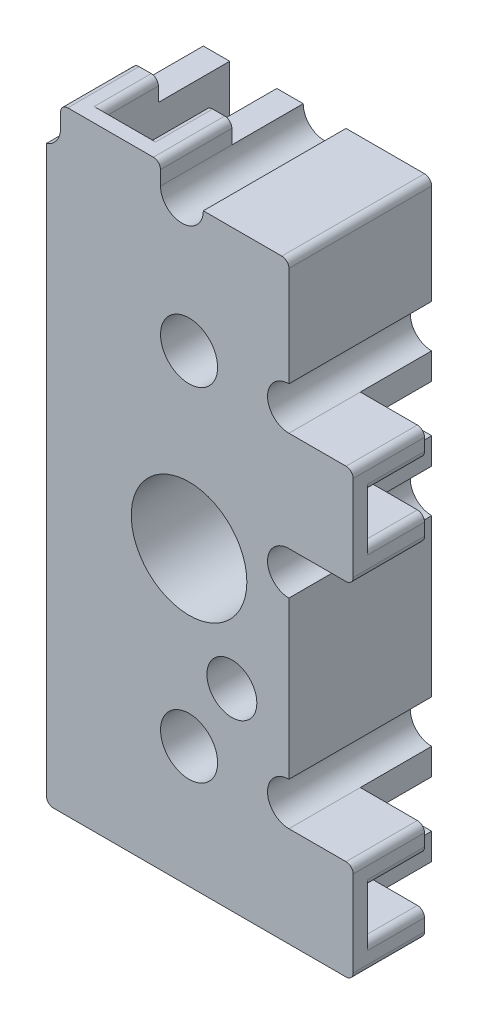
SolidWorks part; units mm, degrees
ref_plane "Front Plane" through (0, 0, 0) normal (0, 0, 1) x (1, 0, 0)
ref_plane "Top Plane" through (0, 0, 0) normal (0, 1, 0) x (1, 0, 0)
ref_plane "Right Plane" through (0, 0, 0) normal (1, 0, 0) x (0, 0, -1)
sketch "Sketch12" plane through (0, 0, 0) normal (0, 0, 1) x (1, 0, 0)
  line L1 (-17, -41.5) -> (0, -41.5)
  line L2 (-17, -41.5) -> (-17, 0)
  line L3 (-17, 0) -> (0, 0)
  line L4 (0, -41.5) -> (0, 0)
  circle A0 centre (-7, -9) radius 2
  circle A1 centre (-7, -21) radius 4.05
  circle A2 centre (-7, -33) radius 2
  circle A3 centre (-4, -28) radius 1.75
  dimension "D1" = 8.1
  dimension "D2" = 4
  dimension "D9" = 3.5
  dimension "D3" = 12
  dimension "D4" = 9
  dimension "D5" = 7
  dimension "D6" = 17
  dimension "D7" = 8.5
  dimension "D8" = 12
  dimension "D10" = 4
  dimension "D12" = 28
extrude "Boss-Extrude3" add sketch "Sketch12" along normal blind 10
sketch "Sketch18" plane through (0, 0, 10) normal (0, 0, 1) x (1, 0, 0)
  line L0 (0, -41.5) -> (0, 0) construction
  line L1 (0, -10.5) -> (4.5, -10.5)
  line L2 (0, -10.5) -> (0, -17.5)
  line L3 (0, -17.5) -> (4.5, -17.5)
  line L4 (4.5, -10.5) -> (4.5, -17.5)
  line L5 (-17, -41.5) -> (0, -41.5) construction
  line L6 (0, -34.5) -> (4.5, -34.5)
  line L7 (0, -34.5) -> (0, -41.5)
  line L8 (0, -41.5) -> (4.5, -41.5)
  line L9 (4.5, -34.5) -> (4.5, -41.5)
  line L10 (2.25, -17.5) -> (2.25, -34.5) construction
  line L11 (0, 0) -> (-17, 0) construction
  line L13 (-17, 0) -> (-9, 0)
  line L14 (-17, 0) -> (-17, 1.5)
  line L15 (-17, 1.5) -> (-9, 1.5)
  line L16 (-9, 0) -> (-9, 1.5)
  line L17 (0, -14) -> (4.5, -14) construction
  line L18 (0, -38) -> (4.5, -38) construction
  point P12 (2.25, -26)
  dimension "D1" = 7
  dimension "D2" = 7
  dimension "D3" = 24
  dimension "D4" = 4.5
  dimension "D5" = 8
  dimension "D6" = 1.5
extrude "Boss-Extrude4" add sketch "Sketch18" against normal blind 5
sketch "Sketch23" plane through (0, 0, 0) normal (0, 0, -1) x (-1, 0, 0)
  circle A0 centre (4, -28) radius 2
  dimension "D1" = 4
extrude "Cut-Extrude12" cut sketch "Sketch23" against normal blind 2
sketch "Sketch24" plane through (0, 0, 0) normal (0, 0, -1) x (-1, 0, 0)
  line L0 (17, 1.5) -> (17, 0) construction
  line L16 (0, -33) -> (-4.5, -33) construction
  line L17 (0, -41.5) -> (0, 0) construction
  line L18 (0, -34.5) -> (-4.5, -34.5)
  line L19 (-4.5, -17.5) -> (-4.5, -10.5) construction
  line L20 (0, -31.5) -> (-4.5, -31.5)
  line L21 (-4.5, -34.5) -> (0, -34.5) construction
  line L22 (-4.5, -41.5) -> (-4.5, -34.5) construction
  line L23 (0, -19) -> (-4.5, -19) construction
  line L24 (0, -20.5) -> (-4.5, -20.5)
  line L25 (0, -17.5) -> (-4.5, -17.5)
  line L26 (0, -17.5) -> (-4.5, -17.5) construction
  line L27 (-4.5, -9) -> (0, -9) construction
  line L28 (-4.5, -7.5) -> (0, -7.5)
  line L29 (-4.5, -10.5) -> (0, -10.5)
  line L30 (-4.5, -10.5) -> (0, -10.5) construction
  line L31 (7.5, 0) -> (7.5, 1.5) construction
  line L32 (0, 0) -> (17, 0) construction
  line L33 (6, 0) -> (6, 1.5)
  line L34 (9, 0) -> (9, 1.5)
  line L36 (12.5, 1.5) -> (12.5, 7.7595) construction
  line L37 (17.5, 0) -> (17.5, 1.5) construction
  line L38 (19, 0) -> (19, 1.5)
  line L39 (16, 0) -> (16, 1.5)
  line L40 (9, 0) -> (9, 1.5) construction
  line L41 (9, 1.5) -> (17, 1.5) construction
  arc A6 (0, -34.5) -> (0, -31.5) centre (0, -33) ccw
  arc A7 (-4.5, -31.5) -> (-4.5, -34.5) centre (-4.5, -33) ccw
  arc A8 (0, -20.5) -> (0, -17.5) centre (0, -19) ccw
  arc A9 (-4.5, -17.5) -> (-4.5, -20.5) centre (-4.5, -19) ccw
  arc A10 (-4.5, -7.5) -> (-4.5, -10.5) centre (-4.5, -9) ccw
  arc A11 (0, -10.5) -> (0, -7.5) centre (0, -9) ccw
  arc A12 (6, 0) -> (9, 0) centre (7.5, 0) ccw
  arc A13 (9, 1.5) -> (6, 1.5) centre (7.5, 1.5) ccw
  arc A14 (19, 0) -> (16, 0) centre (17.5, 0) cw
  arc A15 (16, 1.5) -> (19, 1.5) centre (17.5, 1.5) cw
  point P26 (8.4756, -8.8449)
  point P42 (-2.25, -33)
  point P53 (-2.25, -19)
  point P64 (-2.25, -9)
  point P75 (7.5, 0.75)
  point P86 (17.5, 0.75)
  dimension "D1" = 4.5
  dimension "D7" = 3
extrude "Cut-Extrude13" cut sketch "Sketch24" against normal through all
sketch "Sketch25" plane through (0, 0, 0) normal (0, 0, -1) x (-1, 0, 0)
  line L0 (12.5, 1.5) -> (12.5, -6.35) construction
  line L1 (14.15, 1.5) -> (14.15, -6.35)
  line L2 (10.85, 1.5) -> (10.85, -6.35)
  line L3 (-4.5, -14) -> (3.35, -14) construction
  line L4 (-4.5, -12.35) -> (3.35, -12.35)
  line L5 (-4.5, -15.65) -> (3.35, -15.65)
  line L6 (-4.5, -38) -> (3.35, -38) construction
  line L7 (-4.5, -36.35) -> (3.35, -36.35)
  line L8 (-4.5, -39.65) -> (3.35, -39.65)
  line L9 (-4.5, -17.5) -> (-4.5, -10.5) construction
  line L10 (-4.5, -41.5) -> (-4.5, -34.5) construction
  line L11 (9, 1.5) -> (16, 1.5) construction
  line L12 (9, 0) -> (9, 1.5) construction
  line L13 (16, 1.5) -> (16, 0) construction
  line L14 (0, -41.5) -> (-4.5, -41.5) construction
  line L15 (-4.5, -34.5) -> (0, -34.5) construction
  line L16 (0, -17.5) -> (-4.5, -17.5) construction
  line L17 (-4.5, -10.5) -> (0, -10.5) construction
  arc A0 (14.15, 1.5) -> (10.85, 1.5) centre (12.5, 1.5) ccw
  arc A1 (10.85, -6.35) -> (14.15, -6.35) centre (12.5, -6.35) ccw
  arc A2 (-4.5, -12.35) -> (-4.5, -15.65) centre (-4.5, -14) ccw
  arc A3 (3.35, -15.65) -> (3.35, -12.35) centre (3.35, -14) ccw
  arc A4 (-4.5, -36.35) -> (-4.5, -39.65) centre (-4.5, -38) ccw
  arc A5 (3.35, -39.65) -> (3.35, -36.35) centre (3.35, -38) ccw
  point P2 (12.5, -2.425)
  point P7 (-0.575, -14)
  point P14 (-0.575, -38)
  dimension "D3" = 3.3
  dimension "D4" = 7.85
extrude "Cut-Extrude14" cut sketch "Sketch25" against normal blind 9
fillet "Fillet4" radius 0.5 14 edges at (4.5, -41.5, 7.5) (4.5, -10.5, 7.5) (4.5, -34.5, 7.5) (4.5, -17.5, 7.5) (-17, -41.5, 5) (0, 0, 5) (-9, 1.5, 7.5) (-16, 1.5, 7.5) (-14.15, 1.5, 7) (-10.85, 1.5, 7) (4.5, -36.35, 7) (4.5, -39.65, 7) (4.5, -15.65, 7) (4.5, -12.35, 7)
